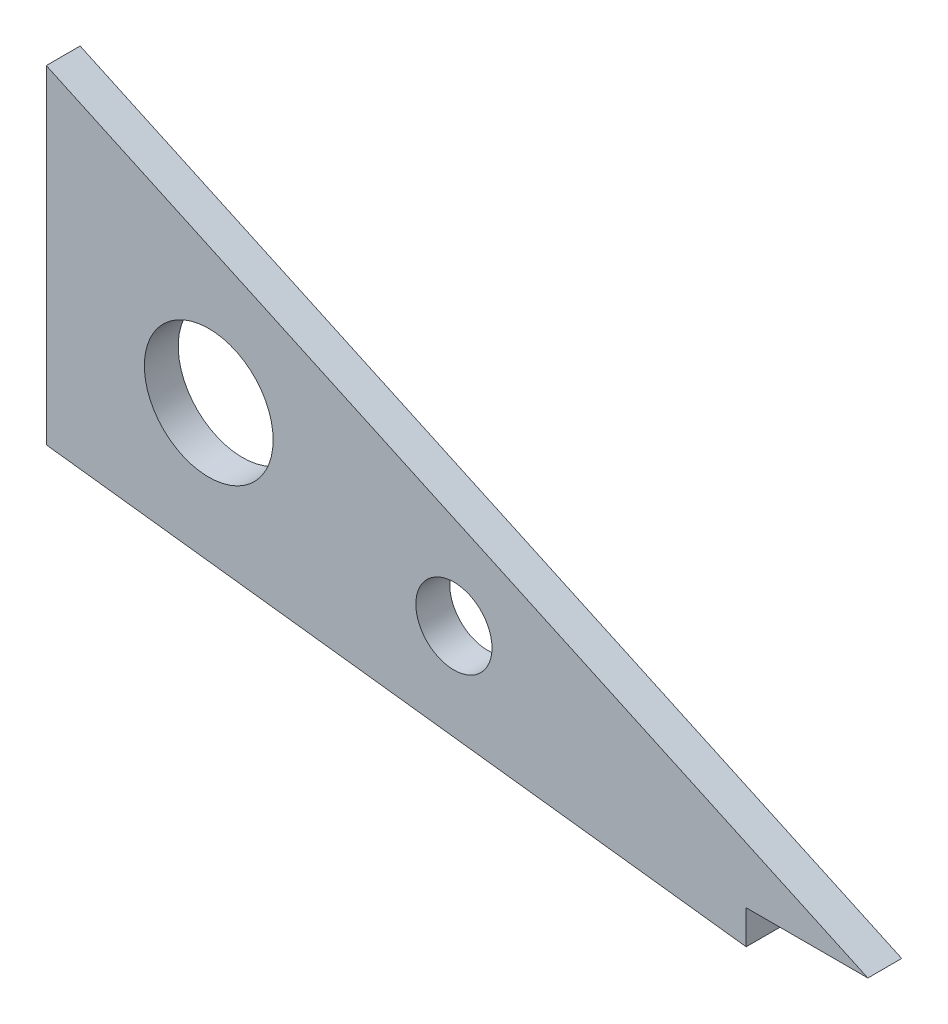
SolidWorks part; units mm, degrees
ref_plane "前视基准面" through (0, 0, 0) normal (0, 0, 1) x (1, 0, 0)
ref_plane "上视基准面" through (0, 0, 0) normal (0, 1, 0) x (1, 0, 0)
ref_plane "右视基准面" through (0, 0, 0) normal (1, 0, 0) x (0, 0, -1)
sketch "Model" plane through (0, 0, 0) normal (0, 0, 1) x (1, 0, 0)
  line L0 (18.3812, 35.3626) -> (18.3812, 15.9599)
  line L1 (18.3812, 35.3626) -> (66.9126, 12.9505)
  line L2 (59.7231, 12.9505) -> (66.9126, 12.9505)
  line L3 (59.7231, 10.9505) -> (59.7231, 12.9505)
  line L4 (18.3812, 15.9599) -> (59.7231, 10.9505)
  circle A0 centre (27.9786, 22.9071) radius 3.8042
  circle A1 centre (42.4603, 18.7298) radius 2.2499
extrude "凸台-拉伸1" add sketch "Model" along normal blind 2
